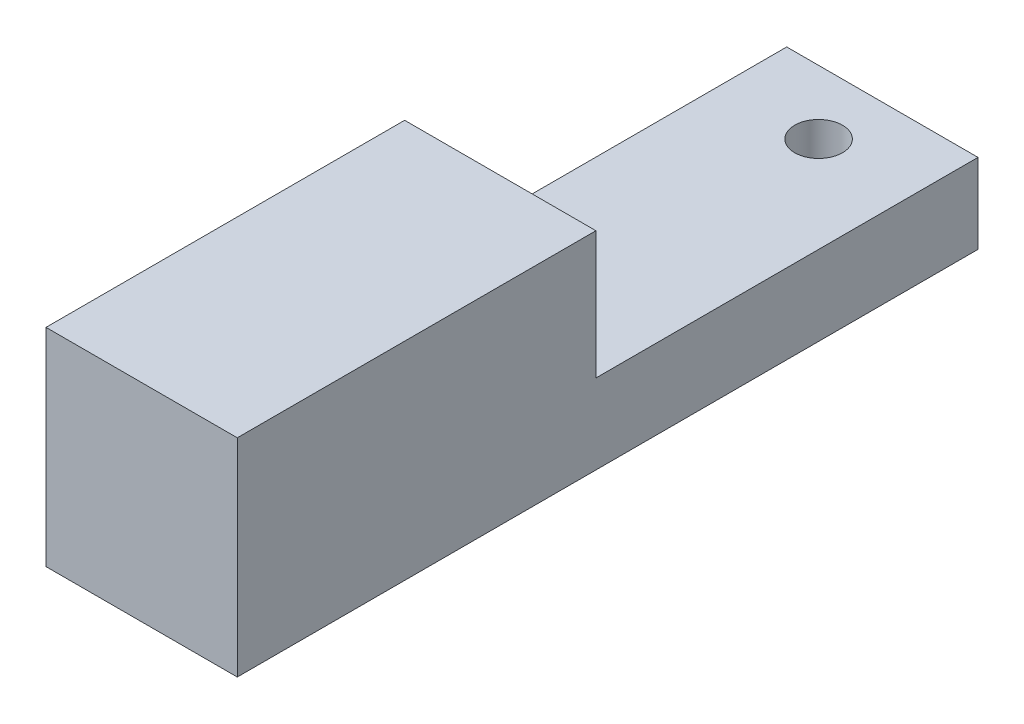
SolidWorks part; units mm, degrees
ref_plane "Front Plane" through (0, 0, 0) normal (0, 0, 1) x (1, 0, 0)
ref_plane "Top Plane" through (0, 0, 0) normal (0, 1, 0) x (1, 0, 0)
ref_plane "Right Plane" through (0, 0, 0) normal (1, 0, 0) x (0, 0, -1)
sketch "Sketch1" plane through (0, 0, 0) normal (0, 1, 0) x (1, 0, 0)
  line L1 (-6, 23.235) -> (6, 23.235)
  line L2 (-6, 23.235) -> (-6, -23.235)
  line L3 (-6, -23.235) -> (6, -23.235)
  line L4 (6, 23.235) -> (6, -23.235)
  circle A0 centre (0, 19.235) radius 1.5
  circle A1 centre (0, 1.765) radius 1.5
  point P8 (-6, 0)
  point P10 (0, 23.235)
  dimension "D1" = 3
  dimension "D2" = 17.47
  dimension "D3" = 4
  dimension "D4" = 6
  dimension "D5" = 25
extrude "Boss-Extrude1" add sketch "Sketch1" against normal blind 5
sketch "Sketch2" plane through (0, 0, 0) normal (0, 1, 0) x (1, 0, 0)
  line L0 (6, -23.235) -> (6, 23.235) construction
  line L1 (-6, -23.235) -> (6, -23.235)
  line L2 (-6, -23.235) -> (-6, -0.735)
  line L3 (-6, -0.735) -> (6, -0.735)
  line L4 (6, -23.235) -> (6, -0.735)
  circle A0 centre (0, 1.765) radius 1.5 construction
  dimension "D1" = 2.5
extrude "Boss-Extrude2" add sketch "Sketch2" along normal blind 8
equation "\"screw\"=3"
equation "\"D1@Sketch1\"=\"screw\""
equation "\"padding\"=4"
equation "\"D3@Sketch1\"=\"padding\""
equation "\"padding_horizontal\"=6"
equation "\"D4@Sketch1\"=\"padding_horizontal\""
